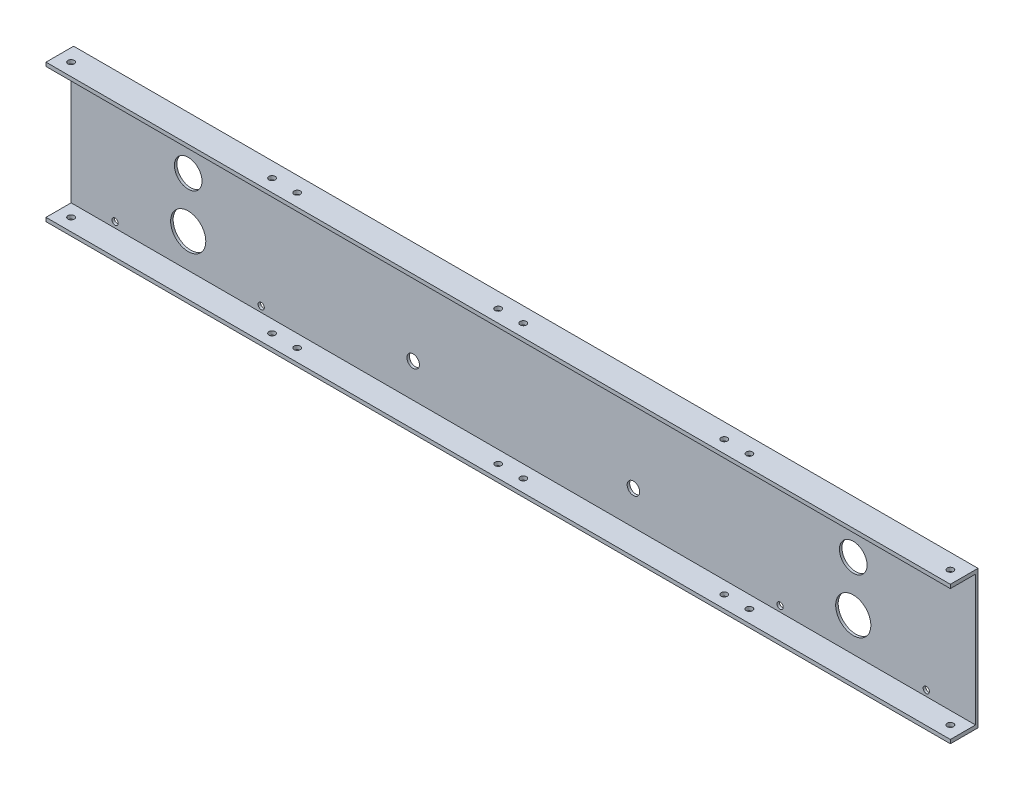
SolidWorks part; units mm, degrees
material "6061-O (SS)"
ref_plane "前视基准面" through (0, 0, 0) normal (0, 0, 1) x (1, 0, 0)
ref_plane "上视基准面" through (0, 0, 0) normal (0, 1, 0) x (1, 0, 0)
ref_plane "右视基准面" through (0, 0, 0) normal (1, 0, 0) x (0, 0, -1)
sketch "草图1" plane through (0, 0, 0) normal (0, 0, 1) x (1, 0, 0)
  line L0 (-93.2193, 74.5194) -> (626.7807, 74.5194)
  line L2 (626.7807, 74.5194) -> (626.7807, -35.4806)
  line L4 (626.7807, -35.4806) -> (-93.2193, -35.4806)
  line L10 (-93.2193, -35.4806) -> (-93.2193, 74.5194)
  circle A0 centre (529.4665, 34.5194) radius 11
  circle A2 centre (0, 34.5194) radius 11
  circle A3 centre (0, -5.4806) radius 14
  circle A4 centre (58.1177, -27.9306) radius 2.5
  circle A5 centre (58.25, 59.9694) radius 2.5
  circle A6 centre (-58.25, 59.9694) radius 2.5
  circle A7 centre (179.095, -5.4806) radius 5
  circle A8 centre (354.4665, -5.4806) radius 5
  circle A9 centre (-58.25, -27.9306) radius 2.5
  circle A10 centre (529.4665, -5.4806) radius 14
  circle A11 centre (587.5842, -27.9306) radius 2.5
  circle A12 centre (587.7165, 59.9694) radius 2.5
  circle A13 centre (471.2165, 59.9694) radius 2.5
  circle A14 centre (471.2165, -27.9306) radius 2.5
extrude "凸台-拉伸1" add sketch "草图1" along normal blind 2
sketch "草图2" plane through (0, 0, 2) normal (0, 0, 1) x (1, 0, 0)
  line L0 (626.7807, -35.4806) -> (626.7807, 74.5194) construction
  line L1 (-93.2193, 74.5194) -> (626.7807, 74.5194)
  line L2 (-93.2193, 74.5194) -> (-93.2193, 71.5194)
  line L3 (-93.2193, 71.5194) -> (626.7807, 71.5194)
  line L4 (626.7807, 74.5194) -> (626.7807, 71.5194)
  line L6 (-93.2193, -35.4806) -> (626.7807, -35.4806)
  line L7 (-93.2193, -35.4806) -> (-93.2193, -32.4806)
  line L8 (-93.2193, -32.4806) -> (626.7807, -32.4806)
  line L9 (626.7807, -35.4806) -> (626.7807, -32.4806)
extrude "凸台-拉伸2" add sketch "草图2" along normal blind 20
sketch "草图3" plane through (0, 74.5194, 0) normal (0, 1, 0) x (1, 0, 0)
  circle A1 centre (456.7807, -12) radius 2.5
  circle A2 centre (616.7807, -12) radius 2.5
  circle A3 centre (436.7807, -12) radius 2.5
  circle A4 centre (276.7807, -12) radius 2.5
  circle A5 centre (256.7807, -12) radius 2.5
  circle A6 centre (96.7807, -12) radius 2.5
  circle A7 centre (76.7807, -12) radius 2.5
  circle A8 centre (-83.2193, -12) radius 2.5
extrude "切除-拉伸3" cut sketch "草图3" against normal blind 114
